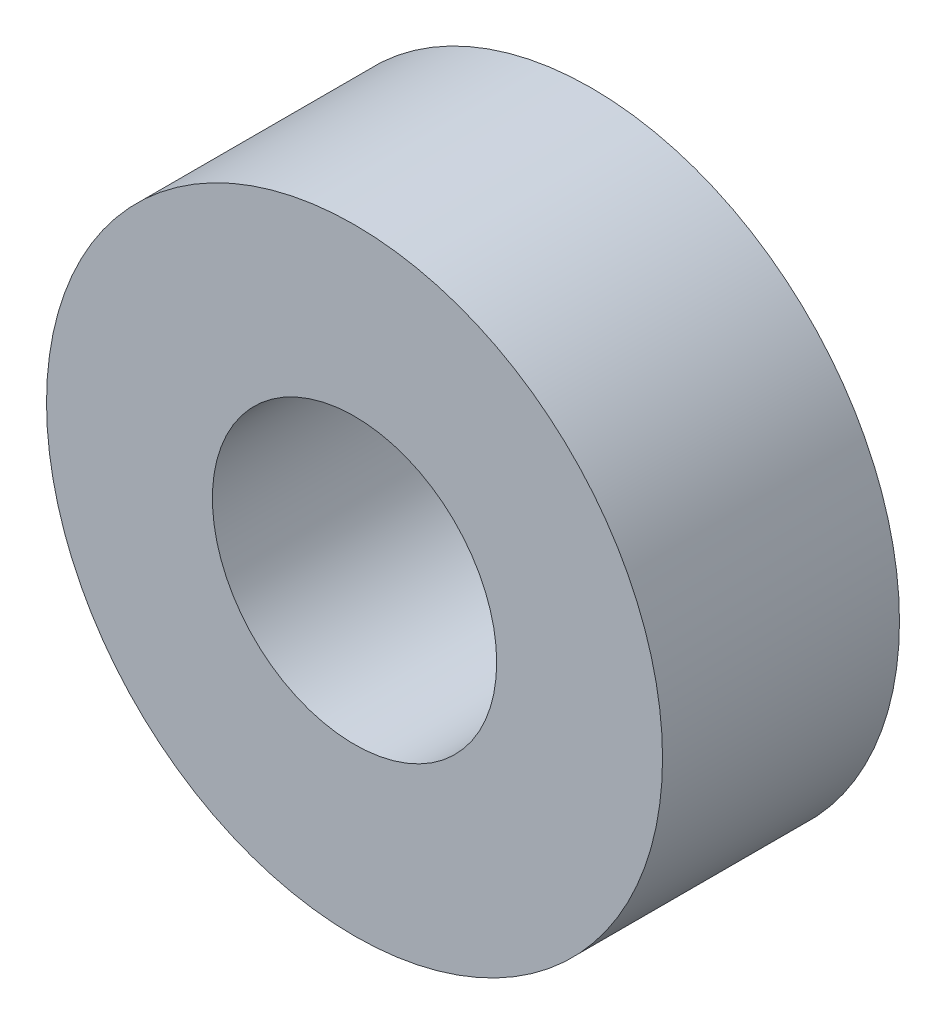
SolidWorks part; units mm, degrees
material "Chrome Stainless Steel"
ref_plane "Front Plane" through (0, 0, 0) normal (0, 0, 1) x (1, 0, 0)
ref_plane "Top Plane" through (0, 0, 0) normal (0, 1, 0) x (1, 0, 0)
ref_plane "Right Plane" through (0, 0, 0) normal (1, 0, 0) x (0, 0, -1)
sketch "Sketch2" plane through (0, 0, 0) normal (0, 0, 1) x (1, 0, 0)
  circle A0 centre (0, 0) radius 6.5
  circle A1 centre (0, 0) radius 3
  dimension "D1" = 13
  dimension "D2" = 6
extrude "Boss-Extrude1" add sketch "Sketch2" along normal blind 5
